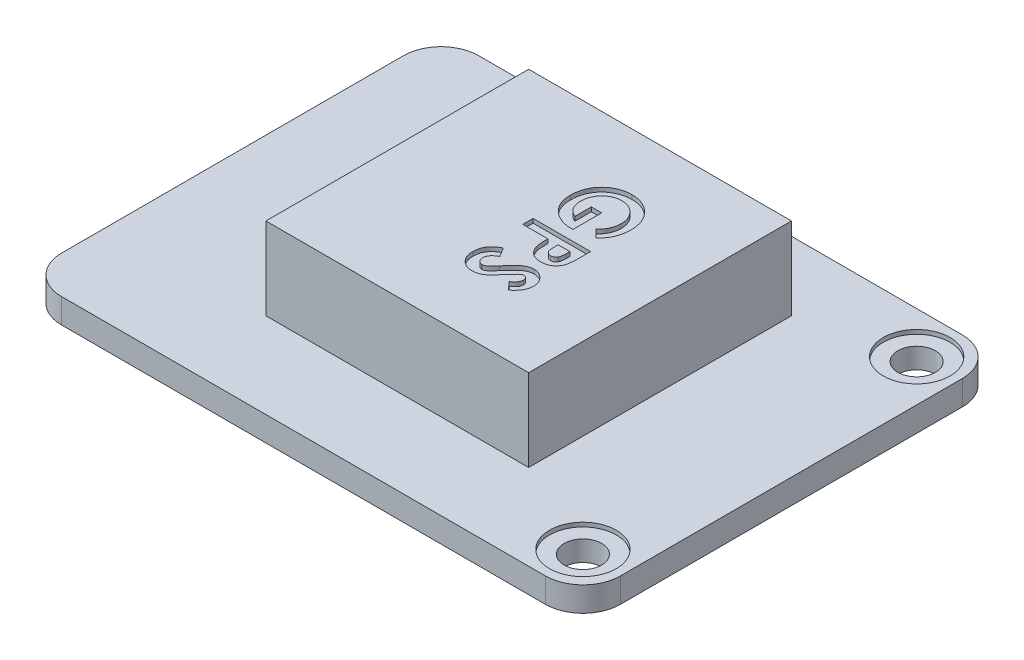
SolidWorks part; units mm, degrees
ref_plane "Front Plane" through (0, 0, 0) normal (0, 0, 1) x (1, 0, 0)
ref_plane "Top Plane" through (0, 0, 0) normal (0, 1, 0) x (1, 0, 0)
ref_plane "Right Plane" through (0, 0, 0) normal (1, 0, 0) x (0, 0, -1)
sketch "Sketch1" plane through (0, 0, 0) normal (0, 1, 0) x (1, 0, 0)
  line L0 (0, 0) -> (50000, 0) construction
  line L1 (-17.018, -12.7) -> (17.018, -12.7)
  line L2 (-17.018, -12.7) -> (-17.018, 12.7)
  line L3 (-17.018, 12.7) -> (17.018, 12.7)
  line L4 (17.018, -12.7) -> (17.018, 12.7)
  line L5 (-17.018, -12.7) -> (17.018, 12.7) construction
  line L6 (-17.018, 12.7) -> (17.018, -12.7) construction
  line L10 (14.478, -10.16) -> (14.478, 10.16) construction
  circle A0 centre (14.478, 10.16) radius 1.143
  circle A1 centre (14.478, -10.16) radius 1.143
  point P0 (0, 0)
  point P6 (0, 0)
  point P13 (14.0988, 8.1361)
  point P14 (14.478, 0)
  dimension "D5" = 2.286
  dimension "D1" = 25.4
  dimension "D2" = 34.036
  dimension "D3" = 31.496
  dimension "D4" = 20.32
extrude "Boss-Extrude1" add sketch "Sketch1" along normal blind 1.5
sketch "Sketch2" plane through (0, 1.5, 0) normal (0, 1, 0) x (1, 0, 0)
  circle A0 centre (14.478, 10.16) radius 2.032
  circle A1 centre (14.478, 10.16) radius 1.143 construction
  circle A2 centre (14.478, 10.16) radius 1.143
  circle A3 centre (14.478, -10.16) radius 2.032
  circle A4 centre (14.478, -10.16) radius 1.143 construction
  circle A5 centre (14.478, -10.16) radius 1.143
  dimension "D1" = 4.064
extrude "Cut-Extrude3" cut sketch "Sketch2" against normal blind 0.254
sketch "Sketch3" plane through (0, 1.5, 0) normal (0, 1, 0) x (1, 0, 0)
  line L0 (17.018, 12.7) -> (-17.018, 12.7) construction
  line L1 (-7.492, -7.492) -> (8.508, -7.492)
  line L2 (-7.492, -7.492) -> (-7.492, 8.508)
  line L3 (-7.492, 8.508) -> (8.508, 8.508)
  line L4 (8.508, -7.492) -> (8.508, 8.508)
  line L5 (-7.492, -7.492) -> (8.508, 8.508) construction
  line L6 (-7.492, 8.508) -> (8.508, -7.492) construction
  line L7 (-17.018, 12.7) -> (-17.018, -12.7) construction
  point P0 (0.508, 0.508)
  dimension "D1" = 12.192
  dimension "D2" = 17.526
  dimension "D3" = 16
  dimension "D4" = 16
extrude "Boss-Extrude2" add sketch "Sketch3" along normal blind 5
sketch "Sketch4" plane through (0, 6.5, 0) normal (0, 1, 0) x (1, 0, 0)
  line L0 (0.508, 8.508) -> (0.508, -7.492) construction
  line L1 (8.508, 8.508) -> (-7.492, 8.508) construction
  line L2 (-7.492, -7.492) -> (8.508, -7.492) construction
  text T0 "<b>GPS</b>"
extrude "Cut-Extrude4" cut sketch "Sketch4" against normal blind 0.254
fillet "Fillet1" radius 2.286 4 edges at (17.018, 0.75, -12.7) (17.018, 0.75, 12.7) (-17.018, 0.75, -12.7) (-17.018, 0.75, 12.7)
